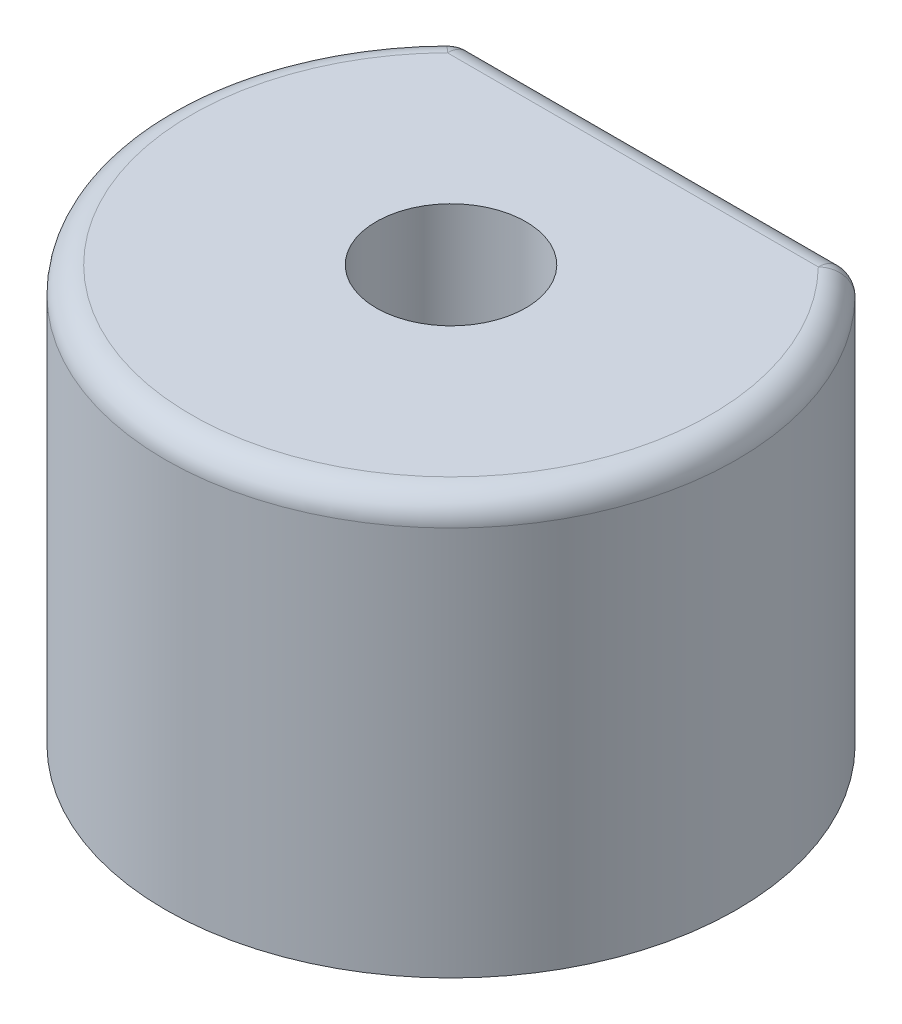
SolidWorks part; units mm, degrees
ref_plane "Front Plane" through (0, 0, 0) normal (0, 0, 1) x (1, 0, 0)
ref_plane "Top Plane" through (0, 0, 0) normal (0, 1, 0) x (1, 0, 0)
ref_plane "Right Plane" through (0, 0, 0) normal (1, 0, 0) x (0, 0, -1)
sketch "Sketch1" plane through (0, 0, 0) normal (0, 1, 0) x (1, 0, 0)
  line L0 (5.9927, 6.35) -> (-5.9927, 6.35)
  arc A0 (-5.9927, 6.35) -> (5.9927, 6.35) centre (0, 0) ccw
  circle A1 centre (0, 0) radius 2.286
  dimension "D2" = 17.4625
  dimension "D3" = 4.572
  dimension "D1" = 6.35
extrude "Boss-Extrude1" add sketch "Sketch1" along normal blind 12.7
fillet "Fillet1" radius 0.7937 4 edges at (0, 12.7, 8.7312) (5.9927, 6.35, -6.35) (-5.9927, 6.35, -6.35) (0, 12.7, -6.35)
